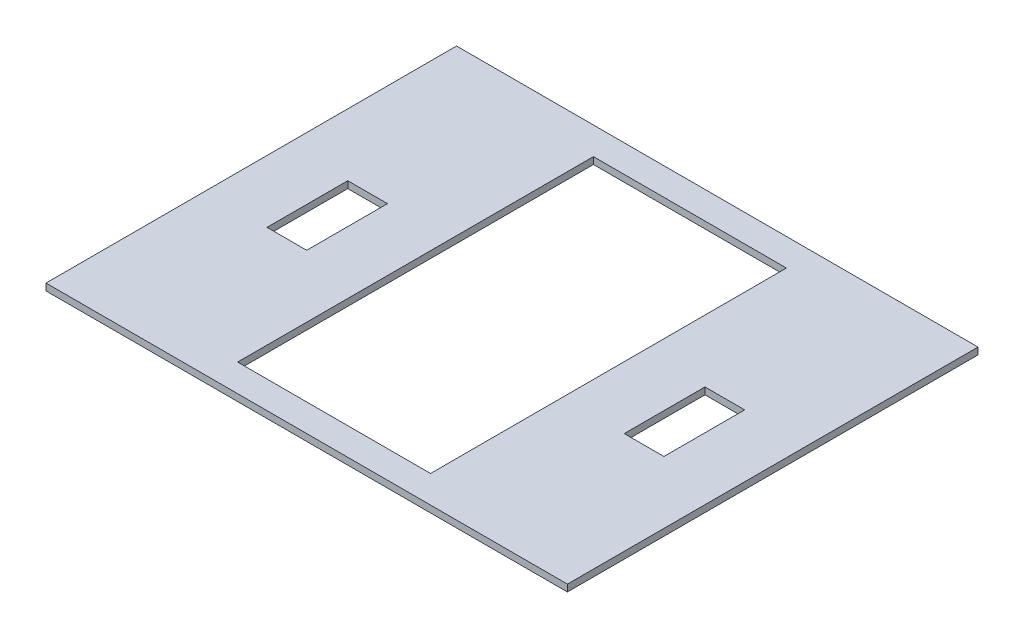
SolidWorks part; units mm, degrees
material "PVC 0.007 Plasticized"
ref_plane "Front Plane" through (0, 0, 0) normal (0, 0, 1) x (1, 0, 0)
ref_plane "Top Plane" through (0, 0, 0) normal (0, 1, 0) x (1, 0, 0)
ref_plane "Right Plane" through (0, 0, 0) normal (1, 0, 0) x (0, 0, -1)
sketch "Sketch1" plane through (0, 0, 0) normal (0, 1, 0) x (1, 0, 0)
  line L1 (0, 0) -> (381, 0)
  line L2 (0, 0) -> (0, 300)
  line L3 (0, 300) -> (381, 300)
  line L4 (381, 0) -> (381, 300)
  dimension "D1" = 300
  dimension "D2" = 381
extrude "Boss-Extrude2" add sketch "Sketch1" along normal blind 5
sketch "Sketch3" plane through (0, 5, 0) normal (0, 1, 0) x (1, 0, 0)
  line L0 (381, 300) -> (0, 300) construction
  line L1 (45.5, 175) -> (74.5, 175)
  line L2 (45.5, 175) -> (45.5, 116)
  line L3 (45.5, 116) -> (74.5, 116)
  line L4 (74.5, 175) -> (74.5, 116)
  line L5 (306.5, 175) -> (335.5, 175)
  line L6 (306.5, 175) -> (306.5, 116)
  line L7 (306.5, 116) -> (335.5, 116)
  line L8 (335.5, 175) -> (335.5, 116)
  line L9 (120, 280) -> (261, 280)
  line L10 (120, 280) -> (120, 20)
  line L11 (120, 20) -> (261, 20)
  line L12 (261, 280) -> (261, 20)
  line L13 (0, 0) -> (381, 0) construction
  line L14 (0, 300) -> (0, 0) construction
  line L15 (381, 0) -> (381, 300) construction
  dimension "D1" = 20
  dimension "D2" = 20
  dimension "D3" = 59
  dimension "D4" = 59
  dimension "D5" = 29
  dimension "D6" = 29
  dimension "D7" = 45.5
  dimension "D8" = 45.5
  dimension "D9" = 116
  dimension "D10" = 116
  dimension "D11" = 120
  dimension "D12" = 120
extrude "Cut-Extrude2" cut sketch "Sketch3" against normal blind 5
